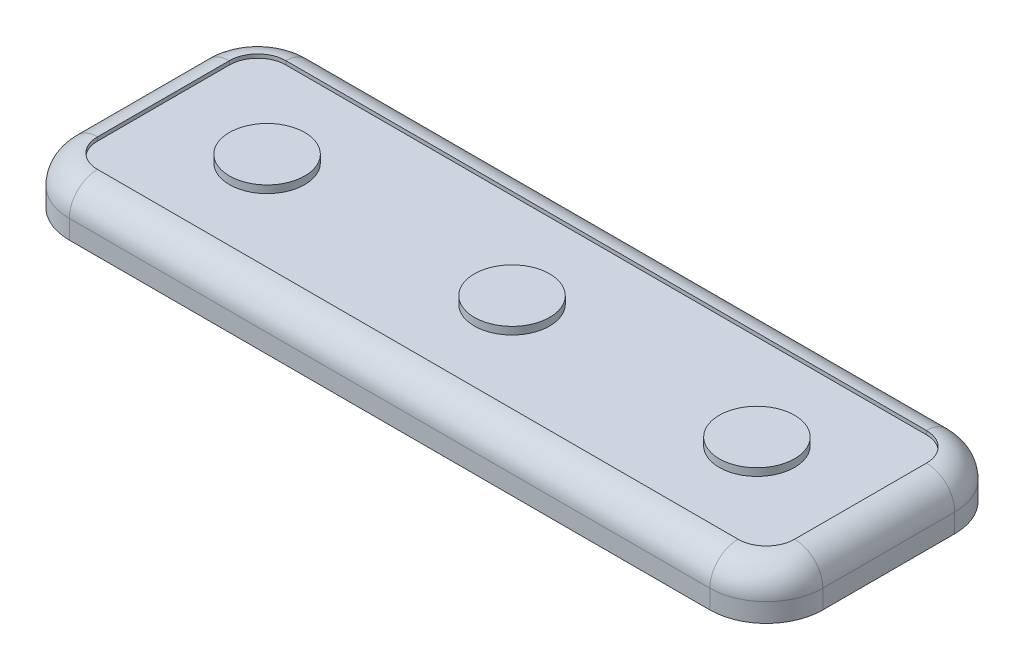
SolidWorks part; units mm, degrees
ref_plane "Front Plane" through (0, 0, 0) normal (0, 0, 1) x (1, 0, 0)
ref_plane "Top Plane" through (0, 0, 0) normal (0, 1, 0) x (1, 0, 0)
ref_plane "Right Plane" through (0, 0, 0) normal (1, 0, 0) x (0, 0, -1)
sketch "Sketch1" plane through (0, 0, 0) normal (0, 1, 0) x (1, 0, 0)
  line L1 (5080, 1651) -> (-5080, 1651)
  line L2 (5080, 1651) -> (5080, -1651)
  line L3 (5080, -1651) -> (-5080, -1651)
  line L4 (-5080, 1651) -> (-5080, -1651)
  dimension "D1" = 10160
  dimension "D2" = 3302
  dimension "D3" = 5080
  dimension "D4" = 1651
extrude "Boss-Extrude1" add sketch "Sketch1" along normal blind 635
fillet "Fillet1" radius 762 4 edges at (-5080, 317.5, -1651) (5080, 317.5, -1651) (5080, 317.5, 1651) (-5080, 317.5, 1651)
fillet "Fillet2" radius 381 8 edges at (4856.8154, 635, -1427.8154) (5080, 635, 0) (4856.8154, 635, 1427.8154) (0, 635, 1651) (-4856.8154, 635, 1427.8154) (-5080, 635, 0) (-4856.8154, 635, -1427.8154) (0, 635, -1651)
shell "Shell1" thickness 101.6
sketch "Sketch3" plane through (4978.4, 0, 0) normal (-1, 0, 0) x (0, 0, 1)
  line L0 (-889, 0) -> (889, 0) construction
  line L1 (0, 0) -> (0, 1206.2086) construction
  circle A0 centre (635, 0) radius 127
  circle A1 centre (-635, 0) radius 127
  dimension "D2" = 254
  dimension "D1" = 635
extrude "Cut-Extrude1" cut sketch "Sketch3" along normal blind 10109.2 and the other way blind 50.8
sketch "Sketch4" plane through (0, 635, 0) normal (0, 1, 0) x (1, 0, 0)
  line L4 (4699, -889) -> (4699, 889)
  line L5 (4318, 1270) -> (-4318, 1270)
  line L6 (-4699, 889) -> (-4699, -889)
  line L7 (-4318, -1270) -> (4318, -1270)
  line L8 (4699, -889) -> (4699, 889)
  line L9 (4318, 1270) -> (-4318, 1270)
  line L10 (-4699, 889) -> (-4699, -889)
  line L11 (-4318, -1270) -> (4318, -1270)
  arc A4 (4699, 889) -> (4318, 1270) centre (4318, 889) ccw
  arc A5 (-4318, 1270) -> (-4699, 889) centre (-4318, 889) ccw
  arc A6 (-4699, -889) -> (-4318, -1270) centre (-4318, -889) ccw
  arc A7 (4318, -1270) -> (4699, -889) centre (4318, -889) ccw
  arc A8 (4699, 889) -> (4318, 1270) centre (4318, 889) ccw
  arc A9 (-4318, 1270) -> (-4699, 889) centre (-4318, 889) ccw
  arc A10 (-4699, -889) -> (-4318, -1270) centre (-4318, -889) ccw
  arc A11 (4318, -1270) -> (4699, -889) centre (4318, -889) ccw
  dimension "D1" = 0
extrude "Cut-Extrude2" cut sketch "Sketch4" against normal blind 50.8
sketch "Sketch5" plane through (0, 584.2, 0) normal (0, 1, 0) x (1, 0, 0)
  circle A0 centre (0, 0) radius 508
  circle A1 centre (3302, 0) radius 508
  circle A2 centre (-3302, 0) radius 508
  point P7 (0, 0)
  dimension "D1" = 1016
  dimension "D2" = 1016
  dimension "D3" = 1016
  dimension "D4" = 3302
  dimension "D5" = 3302
extrude "Boss-Extrude2" add sketch "Sketch5" along normal blind 101.6
